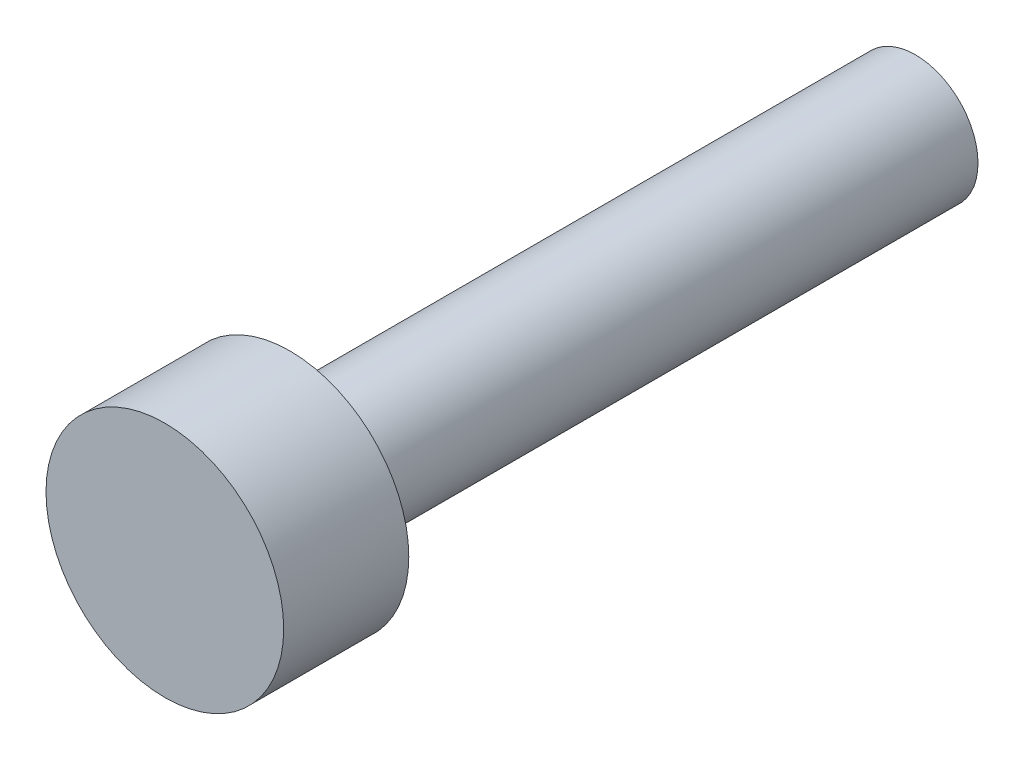
SolidWorks part; units mm, degrees
ref_plane "Front Plane" through (0, 0, 0) normal (0, 0, 1) x (1, 0, 0)
ref_plane "Top Plane" through (0, 0, 0) normal (0, 1, 0) x (1, 0, 0)
ref_plane "Right Plane" through (0, 0, 0) normal (1, 0, 0) x (0, 0, -1)
sketch "Shank_nominal_thread_envelope_profile" plane through (0, 0, 0) normal (0, 0, 1) x (1, 0, 0)
  circle A0 centre (0, 0) radius 1
  dimension "D1" = 2
extrude "Shank_nominal_thread_envelope" add sketch "Shank_nominal_thread_envelope_profile" along normal blind 10 from offset 10
sketch "Socket_head_envelope_profile" plane through (0, 0, 0) normal (0, 0, 1) x (1, 0, 0)
  circle A0 centre (0, 0) radius 1.9
  dimension "D1" = 3.8
extrude "Socket_head_envelope" add sketch "Socket_head_envelope_profile" along normal blind 2
